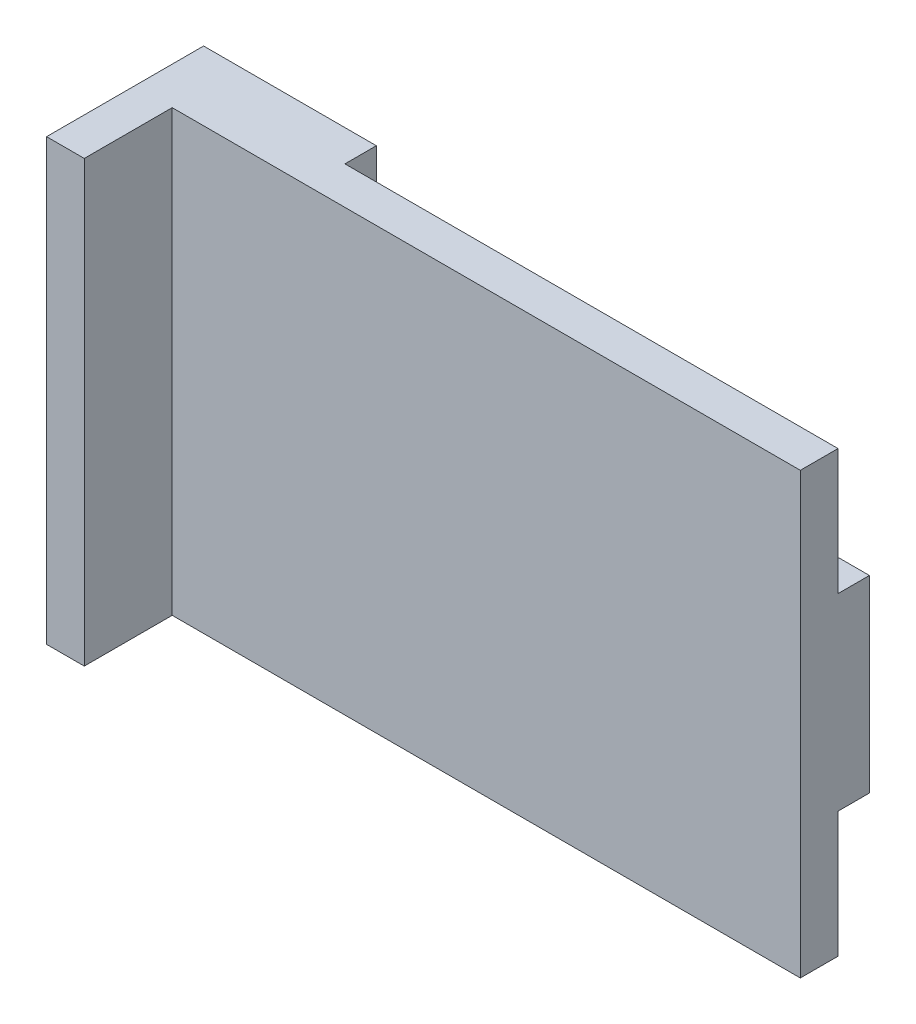
SolidWorks part; units mm, degrees
material "AISI 1010 钢，热轧条材"
ref_plane "前视基准面" through (0, 0, 0) normal (0, 0, 1) x (1, 0, 0)
ref_plane "上视基准面" through (0, 0, 0) normal (0, 1, 0) x (1, 0, 0)
ref_plane "右视基准面" through (0, 0, 0) normal (1, 0, 0) x (0, 0, -1)
sketch "草图1" plane through (0, 0, 0) normal (1, 0, 0) x (0, 0, -1)
  line L0 (0, 0) -> (0, -51259.3873) construction
  line L1 (0, 0) -> (51259.3873, 0) construction
  line L3 (-20, -35) -> (0, -35)
  line L4 (-20, -35) -> (-20, 35)
  line L5 (-20, 35) -> (0, 35)
  line L6 (0, -35) -> (0, 35)
  line L7 (-20, -35) -> (0, 35) construction
  line L8 (-20, 35) -> (0, -35) construction
  point P5 (-10, 0)
  dimension "D1" = 70
  dimension "D2" = 20
extrude "凸台-拉伸1" add sketch "草图1" along normal blind 6
sketch "草图2" plane through (6, 0, 0) normal (1, 0, 0) x (0, 0, -1)
  line L0 (-20, -35) -> (0, -35) construction
  line L1 (0, 35) -> (-6, 35)
  line L2 (0, 35) -> (0, -35)
  line L3 (0, -35) -> (-6, -35)
  line L4 (-6, 35) -> (-6, -35)
  dimension "D1" = 6
extrude "凸台-拉伸2" add sketch "草图2" along normal blind 100
sketch "草图3" plane through (0, 0, 0) normal (0, 0, -1) x (-1, 0, 0)
  line L0 (0, 0) -> (-115.1306, 0) construction
  line L1 (-106, 35) -> (0, 35) construction
  line L2 (0, -35) -> (-27.5, -35)
  line L3 (0, -35) -> (0, 35)
  line L4 (0, 35) -> (-27.5, 35)
  line L5 (-27.5, -35) -> (-27.5, -15)
  line L6 (-27.5, 15) -> (-106, 15)
  line L7 (-106, -35) -> (-106, 35) construction
  line L8 (-106, 15) -> (-106, -15)
  line L9 (-27.5, -15) -> (-106, -15)
  line L10 (-27.5, 15) -> (-27.5, 35)
  point P16 (-106, 0)
  dimension "D1" = 30
  dimension "D3" = 27.5
extrude "凸台-拉伸3" add sketch "草图3" along normal blind 5
